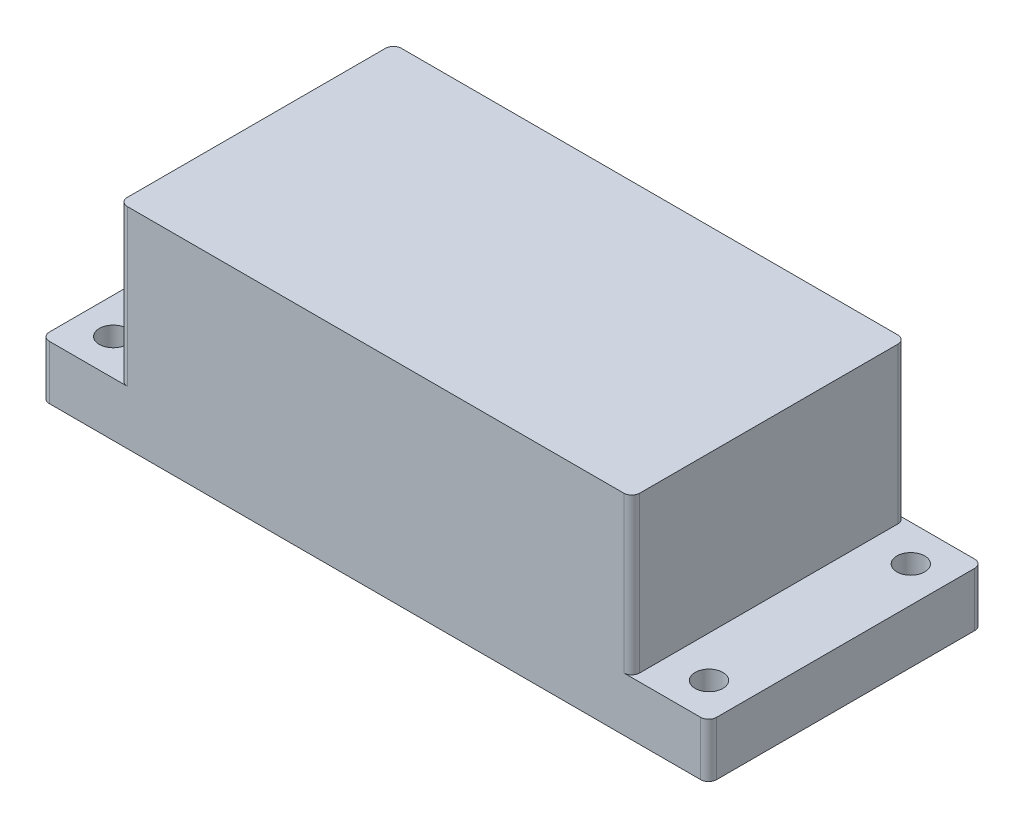
SolidWorks part; units mm, degrees
ref_plane "Front Plane" through (0, 0, 0) normal (0, 0, 1) x (1, 0, 0)
ref_plane "Top Plane" through (0, 0, 0) normal (0, 1, 0) x (1, 0, 0)
ref_plane "Right Plane" through (0, 0, 0) normal (1, 0, 0) x (0, 0, -1)
sketch "Sketch1" plane through (0, 0, 0) normal (0, 1, 0) x (1, 0, 0)
  line L1 (-16.2513, 8.7513) -> (67.7487, 8.7513)
  line L2 (-16.2513, 8.7513) -> (-16.2513, -25.7487)
  line L3 (-16.2513, -25.7487) -> (67.7487, -25.7487)
  line L4 (67.7487, 8.7513) -> (67.7487, -25.7487)
  dimension "D1" = 84
  dimension "D2" = 34.5
extrude "Boss-Extrude1" add sketch "Sketch1" along normal blind 6.8
sketch "Sketch2" plane through (0, 6.8, 0) normal (0, 1, 0) x (1, 0, 0)
  line L0 (67.7487, 8.7513) -> (-16.2513, 8.7513) construction
  line L1 (-6.4253, 8.7513) -> (58.0747, 8.7513)
  line L2 (-6.4253, 8.7513) -> (-6.4253, -25.7487)
  line L3 (-6.4253, -25.7487) -> (58.0747, -25.7487)
  line L4 (58.0747, 8.7513) -> (58.0747, -25.7487)
  line L5 (-16.2513, -25.7487) -> (67.7487, -25.7487) construction
  dimension "D1" = 64.5
extrude "Boss-Extrude2" add sketch "Sketch2" along normal blind 19.6
sketch "Sketch3" plane through (0, 6.8, 0) normal (0, 1, 0) x (1, 0, 0)
  line L0 (67.7487, -25.7487) -> (67.7487, 8.7513) construction
  line L1 (67.7487, 8.7513) -> (58.0747, 8.7513) construction
  line L2 (58.0747, -25.7487) -> (67.7487, -25.7487) construction
  line L3 (-16.2513, 8.7513) -> (-16.2513, -25.7487) construction
  line L4 (-16.2513, -25.7487) -> (-6.4253, -25.7487) construction
  line L5 (-6.4253, 8.7513) -> (-16.2513, 8.7513) construction
  circle A0 centre (63.2487, 4.2013) radius 1.75
  circle A1 centre (63.2487, -21.1987) radius 1.75
  circle A2 centre (-11.7513, -21.1987) radius 1.75
  circle A3 centre (-11.7513, 4.2013) radius 1.75
  point P6 (62.9117, 8.7513)
  dimension "D1" = 4.5
  dimension "D3" = 4.55
  dimension "D5" = 4.5
  dimension "D7" = 4.5
  dimension "D2" = 4.55
  dimension "D4" = 4.5
  dimension "D6" = 4.55
  dimension "D8" = 4.55
extrude "Cut-Extrude1" cut sketch "Sketch3" against normal up to surface (6.8 mm away) up to face at (25.7487, 0, 8.4987)
fillet "Fillet1" radius 1 4 edges at (67.7487, 3.4, -8.7513) (67.7487, 3.4, 25.7487) (-16.2513, 3.4, -8.7513) (-16.2513, 3.4, 25.7487)
fillet "Fillet2" radius 1 4 edges at (58.0747, 16.6, 25.7487) (58.0747, 16.6, -8.7513) (-6.4253, 16.6, -8.7513) (-6.4253, 16.6, 25.7487)
